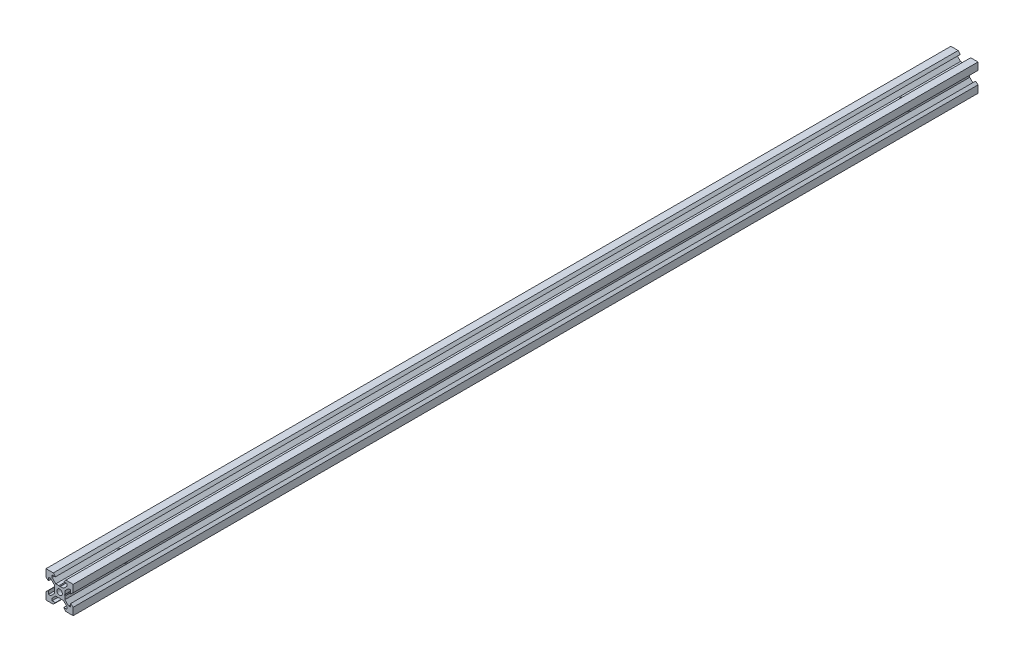
SolidWorks part; units mm, degrees
material "3.3535 (EN-AW 5754)"
ref_plane "Front Plane" through (0, 0, 0) normal (0, 0, 1) x (1, 0, 0)
ref_plane "Top Plane" through (0, 0, 0) normal (0, 1, 0) x (1, 0, 0)
ref_plane "Right Plane" through (0, 0, 0) normal (1, 0, 0) x (0, 0, -1)
sketch "Sketch1" plane through (0, 0, 0) normal (0, 0, 1) x (1, 0, 0)
  line L0 (10, 10) -> (4.6104, 10) construction
  line L1 (10, 10) -> (10, 4.6104) construction
  line L2 (10, -10) -> (10, -4.6104) construction
  line L3 (10, -10) -> (4.6104, -10) construction
  line L4 (10, 10) -> (10, 4.6104)
  line L5 (6.5607, 5.5) -> (8.2, 5.5)
  line L6 (5.5, 8.2) -> (5.5, 6.5607)
  line L7 (10, 10) -> (4.6104, 10)
  line L8 (10, 10) -> (10, 4.6104)
  line L9 (6.5607, 5.5) -> (3.9, 2.8393)
  line L10 (5.5, 6.5607) -> (2.8393, 3.9)
  line L11 (10, 4.6104) -> (8.2, 3.1)
  line L12 (4.6104, 10) -> (3.1, 8.2)
  line L13 (8.2, 3.1) -> (8.2, 5.5)
  line L14 (3.1, 8.2) -> (5.5, 8.2)
  line L15 (-6.5607, 5.5) -> (-8.2, 5.5)
  line L16 (6.5607, -5.5) -> (8.2, -5.5)
  line L17 (3.1, -8.2) -> (5.5, -8.2)
  line L18 (8.2, -3.1) -> (8.2, -5.5)
  line L19 (4.6104, -10) -> (3.1, -8.2)
  line L20 (10, -4.6104) -> (8.2, -3.1)
  line L21 (0.5196, -3.9) -> (0, -3.6)
  line L22 (0.5196, 3.9) -> (0, 3.6)
  line L23 (3.6, 0) -> (3.9, -0.5196)
  line L24 (3.9, 0.5196) -> (3.6, 0)
  line L25 (3.9, 0.5196) -> (3.9, 2.8393)
  line L26 (2.8393, 3.9) -> (0.5196, 3.9)
  line L27 (3.9, -2.8393) -> (3.9, -0.5196)
  line L28 (2.8393, -3.9) -> (0.5196, -3.9)
  line L29 (5.5, -6.5607) -> (2.8393, -3.9)
  line L30 (6.5607, -5.5) -> (3.9, -2.8393)
  line L31 (10, -10) -> (10, -4.6104)
  line L32 (10, -10) -> (4.6104, -10)
  line L33 (5.5, -8.2) -> (5.5, -6.5607)
  line L34 (-6.5607, -5.5) -> (-8.2, -5.5)
  line L35 (10, -10) -> (10, -4.6104)
  line L36 (0, 0) -> (0, 8.2) construction
  line L37 (-10, -10) -> (-4.6104, -10) construction
  line L38 (-10, -10) -> (-10, -4.6104) construction
  line L39 (-10, 10) -> (-10, 4.6104) construction
  line L40 (-10, 10) -> (-4.6104, 10) construction
  line L41 (-10, -10) -> (-10, -4.6104)
  line L43 (-5.5, -8.2) -> (-5.5, -6.5607)
  line L44 (-10, -10) -> (-4.6104, -10)
  line L45 (-10, -10) -> (-10, -4.6104)
  line L46 (-6.5607, -5.5) -> (-3.9, -2.8393)
  line L47 (-5.5, -6.5607) -> (-2.8393, -3.9)
  line L48 (-2.8393, -3.9) -> (-0.5196, -3.9)
  line L49 (-3.9, -2.8393) -> (-3.9, -0.5196)
  line L50 (-2.8393, 3.9) -> (-0.5196, 3.9)
  line L51 (-3.9, 0.5196) -> (-3.9, 2.8393)
  line L52 (-3.9, 0.5196) -> (-3.6, 0)
  line L53 (-3.6, 0) -> (-3.9, -0.5196)
  line L54 (-0.5196, 3.9) -> (0, 3.6)
  line L55 (-0.5196, -3.9) -> (0, -3.6)
  line L56 (-10, -4.6104) -> (-8.2, -3.1)
  line L57 (-4.6104, -10) -> (-3.1, -8.2)
  line L58 (-8.2, -3.1) -> (-8.2, -5.5)
  line L59 (-3.1, -8.2) -> (-5.5, -8.2)
  line L60 (-10, -10) -> (10, -10) construction
  line L61 (-10, -10) -> (-10, 10) construction
  line L62 (-3.1, 8.2) -> (-5.5, 8.2)
  line L63 (-8.2, 3.1) -> (-8.2, 5.5)
  line L64 (-4.6104, 10) -> (-3.1, 8.2)
  line L65 (-10, 4.6104) -> (-8.2, 3.1)
  line L66 (-5.5, 6.5607) -> (-2.8393, 3.9)
  line L67 (-6.5607, 5.5) -> (-3.9, 2.8393)
  line L68 (-10, 10) -> (-10, 4.6104)
  line L69 (-10, 10) -> (-4.6104, 10)
  line L70 (-5.5, 8.2) -> (-5.5, 6.5607)
  line L71 (-10, 10) -> (10, 10) construction
  line L72 (-10, 10) -> (-10, 4.6104)
  line L73 (10, -10) -> (10, 10) construction
  line L74 (-10, -10) -> (10, 10) construction
  line L75 (-10, 10) -> (10, -10) construction
  circle A0 centre (0, 0) radius 2
  dimension "D7" = 4
  dimension "D1" = 20
  dimension "D2" = 5.3896
  dimension "D3" = 4.5
  dimension "D4" = 50
  dimension "D5" = 1.8
  dimension "D6" = 1.5104
  dimension "D8" = 5.5
  dimension "D9" = 120
  dimension "D10" = 0.3
  dimension "D11" = 2.3197
  dimension "D12" = 7.8
  dimension "D13" = 7.8
  dimension "D14" = 1.5
  dimension "D15" = 2.6607
extrude "Boss-Extrude1" add sketch "Sketch1" along normal blind 666 contours L70 L62 L64 L69 L68 L65 L63 L15 L67 L51 L52 L53 L49 L46 L34 L58 L56 L41 L44 L57 L59 L43 L47 L48 L55 L21 L28 L29 L33 L17 L19 L32 L31 L20 L18 L16 L30 L27 L23 L24 L25 L9 L5 L13 L11 L4 L7 L12 L14 L6 L10
sketch "Sketch2" plane through (0, -3.9, 0) normal (0, -1, 0) x (-1, 0, 0)
  line L0 (0, -666) -> (0, -621) construction
  line L1 (0, -666) -> (0, 0) construction
  line L2 (0, 0) -> (0, -45) construction
  circle A0 centre (0, -621) radius 2
  circle A1 centre (0, -45) radius 2
  dimension "D2" = 4
  dimension "D4" = 4
  dimension "D1" = 45
  dimension "D3" = 45
extrude "Cut-Extrude1" cut sketch "Sketch2" against normal through all both and the other way through all
sketch "Sketch3" plane through (3.9, 0, 0) normal (1, 0, 0) x (0, 0, -1)
  line L0 (0, 0) -> (-45, 0) construction
  line L1 (-666, 0) -> (0, 0) construction
  line L2 (-666, 0) -> (-621, 0) construction
  circle A0 centre (-45, 0) radius 2
  circle A1 centre (-621, 0) radius 2
  dimension "D2" = 4
  dimension "D4" = 4
  dimension "D1" = 45
  dimension "D3" = 45
extrude "Cut-Extrude2" cut sketch "Sketch3" against normal through all both
